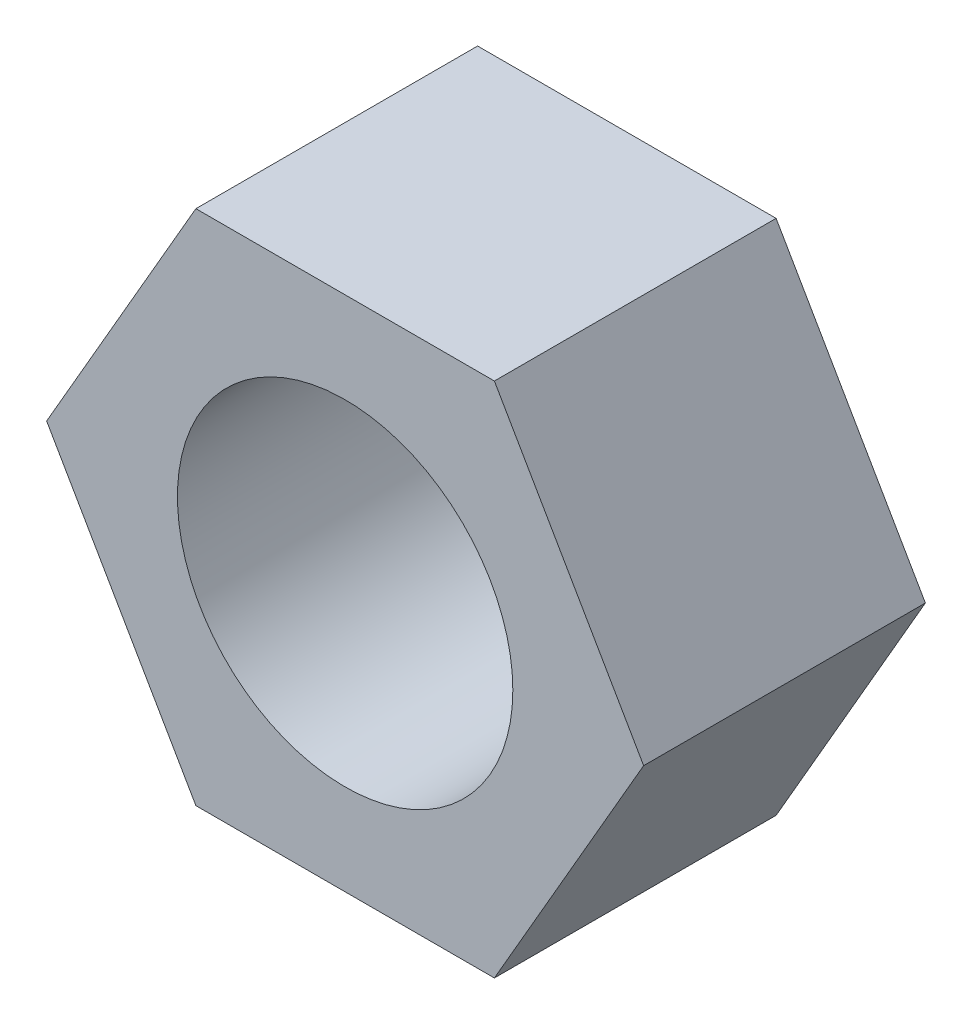
SolidWorks part; units mm, degrees
ref_plane "Płaszczyzna przednia" through (0, 0, 0) normal (0, 0, 1) x (1, 0, 0)
ref_plane "Płaszczyzna górna" through (0, 0, 0) normal (0, 1, 0) x (1, 0, 0)
ref_plane "Płaszczyzna prawa" through (0, 0, 0) normal (1, 0, 0) x (0, 0, -1)
sketch "Sketch1" plane through (0, 0, 0) normal (0, 0, 1) x (1, 0, 0)
  line L1 (8.9, 0) -> (4.45, 7.7076)
  line L2 (4.45, 7.7076) -> (-4.45, 7.7076)
  line L3 (-4.45, 7.7076) -> (-8.9, 0)
  line L4 (-8.9, 0) -> (-4.45, -7.7076)
  line L5 (-4.45, -7.7076) -> (4.45, -7.7076)
  line L6 (4.45, -7.7076) -> (8.9, 0)
  circle A0 centre (0, 0) radius 7.7076 construction
  point P1 (0, 0)
  point P10 (0, 0)
  point P11 (-4.7068, 7.7076)
  point P12 (0, 0)
  point P13 (8.9, 0)
  dimension "e" = 17.8
extrude "Boss-Extrude1" add sketch "Sketch1" along normal blind 8.4
sketch "Sketch2" plane through (0, 0, 8.4) normal (0, 0, 1) x (1, 0, 0)
  circle A0 centre (0, 0) radius 5
  dimension "d" = 10
extrude "Cut-Extrude1" cut sketch "Sketch2" against normal blind 65
